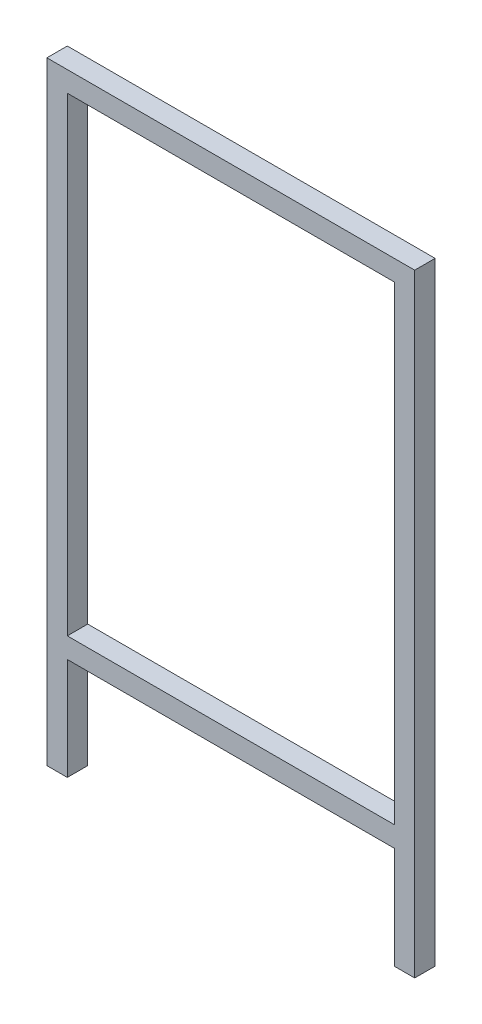
SolidWorks part; units mm, degrees
ref_plane "Front Plane" through (0, 0, 0) normal (0, 0, 1) x (1, 0, 0)
ref_plane "Top Plane" through (0, 0, 0) normal (0, 1, 0) x (1, 0, 0)
ref_plane "Right Plane" through (0, 0, 0) normal (1, 0, 0) x (0, 0, -1)
sketch "Sketch1" plane through (0, 0, 0) normal (0, 0, 1) x (1, 0, 0)
  line L0 (-180, -600) -> (-180, 0)
  line L1 (-180, 0) -> (180, 0)
  line L2 (180, 0) -> (180, -600)
  line L3 (180, -600) -> (160, -600)
  line L4 (160, -600) -> (160, -500)
  line L5 (160, -500) -> (-160, -500)
  line L6 (-160, -500) -> (-160, -600)
  line L7 (-160, -600) -> (-180, -600)
  line L8 (-180, -20) -> (-160, -20) construction
  line L9 (-160, -20) -> (160, -20)
  line L10 (-160, -20) -> (-160, -480)
  line L11 (-160, -480) -> (160, -480)
  line L12 (160, -20) -> (160, -480)
  line L13 (-160, 0) -> (-160, -20) construction
  line L14 (-160, -480) -> (-160, -500) construction
  point P14 (259.3676, -538.345)
  dimension "D1" = 20
  dimension "D2" = 320
  dimension "D3" = 600
  dimension "D4" = 480
extrude "Boss-Extrude1" add sketch "Sketch1" along normal mid plane 20
